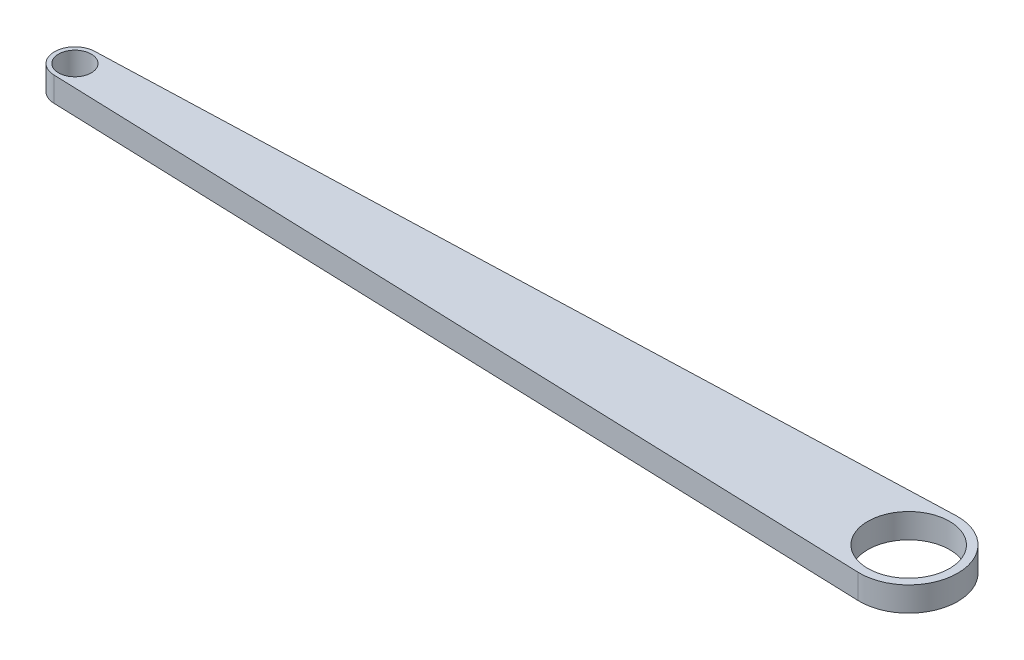
SolidWorks part; units mm, degrees
material "Chromium Copper, UNS C18200"
ref_plane "Front Plane" through (0, 0, 0) normal (0, 0, 1) x (1, 0, 0)
ref_plane "Top Plane" through (0, 0, 0) normal (0, 1, 0) x (1, 0, 0)
ref_plane "Right Plane" through (0, 0, 0) normal (1, 0, 0) x (0, 0, -1)
sketch "Sketch2" plane through (0, 0, 0) normal (0, 1, 0) x (1, 0, 0)
  line L0 (-51.0429, 1.2493) -> (-0.1029, 2.9982)
  line L1 (-51.0429, -1.2493) -> (-0.1029, -2.9982)
  arc A0 (-0.1029, -2.9982) -> (-0.1029, 2.9982) centre (0, 0) ccw
  arc A1 (-51.0429, 1.2493) -> (-51.0429, -1.2493) centre (-51, 0) ccw
  dimension "D1" = 6
  dimension "D2" = 2.5
  dimension "D3" = 51
extrude "Boss-Extrude1" add sketch "Sketch2" along normal mid plane 1.5
sketch "Sketch3" plane through (0, 0.75, 0) normal (0, 1, 0) x (1, 0, 0)
  circle A0 centre (0, 0) radius 2.5
  circle A1 centre (-51, 0) radius 1
extrude "Cut-Extrude1" cut sketch "Sketch3" against normal up to next
ref_plane "Plane1" through (0, 0, 5) normal (0, 0, 1) x (1, 0, 0)
